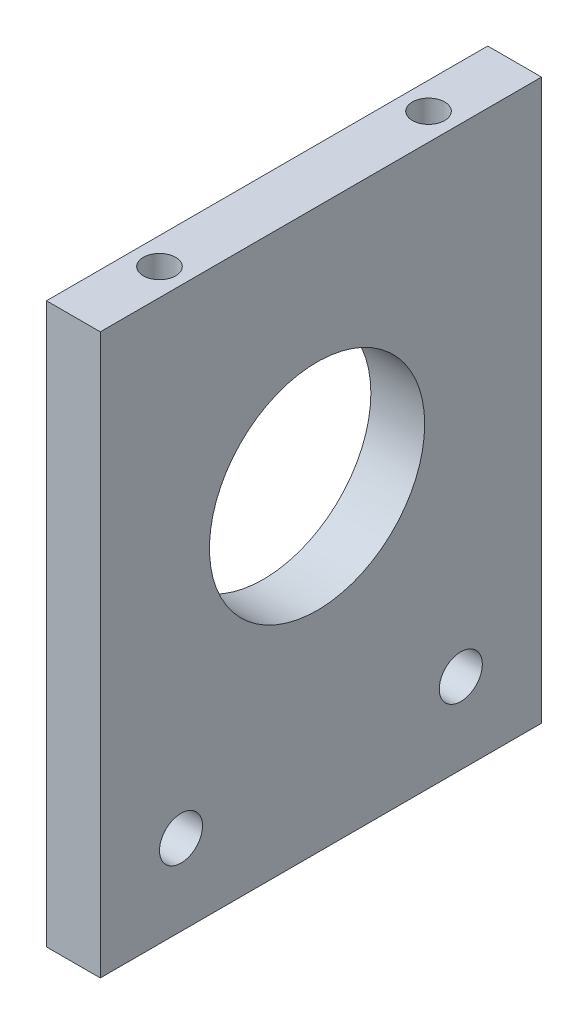
SolidWorks part; units mm, degrees
ref_plane "Front Plane" through (0, 0, 0) normal (0, 0, 1) x (1, 0, 0)
ref_plane "Top Plane" through (0, 0, 0) normal (0, 1, 0) x (1, 0, 0)
ref_plane "Right Plane" through (0, 0, 0) normal (1, 0, 0) x (0, 0, -1)
sketch "Sketch1" plane through (0, 0, 0) normal (1, 0, 0) x (0, 0, -1)
  line L1 (0, 0) -> (41, 0)
  line L2 (0, 0) -> (0, 52)
  line L3 (0, 52) -> (41, 52)
  line L4 (41, 0) -> (41, 52)
  circle A0 centre (7.5, 7.5) radius 2
  circle A1 centre (33.5, 7.5) radius 2
  circle A2 centre (20.143, 29.5) radius 10
  dimension "D3" = 4
  dimension "D4" = 4
  dimension "D9" = 20
  dimension "D1" = 41
  dimension "D2" = 52
  dimension "D5" = 7.5
  dimension "D6" = 7.5
  dimension "D7" = 7.5
  dimension "D8" = 7.5
  dimension "D10" = 22.5
extrude "Boss-Extrude1" add sketch "Sketch1" along normal blind 5
sketch "Sketch2" plane through (0, 0, 0) normal (0, -1, 0) x (-1, 0, 0)
  line L0 (-5, 0) -> (-5, 41) construction
  line L1 (-5, 0) -> (0, 0) construction
  line L2 (-5, 41) -> (0, 41) construction
  circle A0 centre (-2.5, 13) radius 1.5
  circle A1 centre (-2.5, 28) radius 1.5
  dimension "D1" = 3
  dimension "D2" = 3
  dimension "D3" = 2.5
  dimension "D4" = 2.5
  dimension "D5" = 13
  dimension "D6" = 13
extrude "Cut-Extrude1" cut sketch "Sketch2" against normal blind 7
sketch "Sketch3" plane through (0, 52, 0) normal (0, 1, 0) x (1, 0, 0)
  line L0 (5, 41) -> (5, 0) construction
  line L1 (5, 0) -> (0, 0) construction
  line L2 (5, 41) -> (0, 41) construction
  circle A0 centre (2.5, 8) radius 1.5
  circle A1 centre (2.5, 33) radius 1.5
  point P8 (2.5, 41)
  dimension "D1" = 3
  dimension "D2" = 3
  dimension "D3" = 2.5
  dimension "D4" = 2.5
  dimension "D5" = 8
  dimension "D6" = 8
extrude "Cut-Extrude2" cut sketch "Sketch3" against normal blind 7
